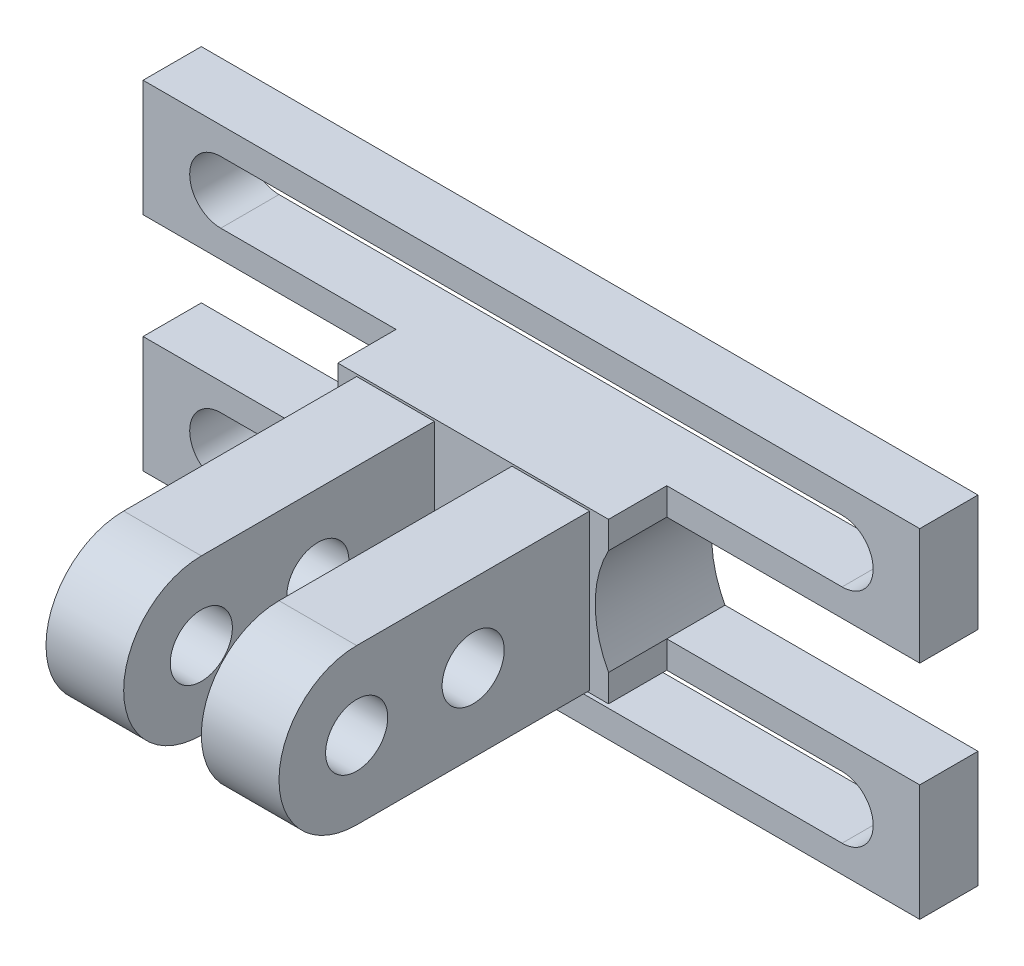
SolidWorks part; units mm, degrees
ref_plane "前视基准面" through (0, 0, 0) normal (0, 0, 1) x (1, 0, 0)
ref_plane "上视基准面" through (0, 0, 0) normal (0, 1, 0) x (1, 0, 0)
ref_plane "右视基准面" through (0, 0, 0) normal (1, 0, 0) x (0, 0, -1)
other "Configuration Table"
sketch "草图1" plane through (0, 0, 0) normal (0, 0, 1) x (1, 0, 0)
  line L0 (30.1537, 0) -> (-30.0932, 0) construction
  line L1 (0, -18.3903) -> (0, 24.264) construction
  line L2 (20, 8.715) -> (20, 2.715)
  line L3 (20, 8.715) -> (-20, 8.715)
  line L5 (20, 2.715) -> (6.9711, 2.715)
  line L6 (-20, 8.715) -> (-20, 2.715)
  line L7 (-20, -8.715) -> (-20, -2.715)
  line L8 (20, -2.715) -> (6.9711, -2.715)
  line L9 (20, -8.715) -> (-20, -8.715)
  line L10 (20, -8.715) -> (20, -2.715)
  line L11 (20, 5.715) -> (-20, 5.715) construction
  line L12 (20, -5.715) -> (-20, -5.715) construction
  line L13 (16, 5.715) -> (-16, 5.715) construction
  line L14 (16, 4.115) -> (-16, 4.115)
  line L15 (16, 7.315) -> (-16, 7.315)
  line L16 (16, -5.715) -> (-16, -5.715) construction
  line L17 (16, -7.315) -> (-16, -7.315)
  line L18 (16, -4.115) -> (-16, -4.115)
  line L21 (-6.9711, 2.715) -> (-20, 2.715)
  line L22 (-6.9711, -2.715) -> (-20, -2.715)
  arc A0 (16, 4.115) -> (16, 7.315) centre (16, 5.715) ccw
  arc A1 (-16, 7.315) -> (-16, 4.115) centre (-16, 5.715) ccw
  arc A2 (16, -7.315) -> (16, -4.115) centre (16, -5.715) ccw
  arc A3 (-16, -4.115) -> (-16, -7.315) centre (-16, -5.715) ccw
  arc A4 (-6.9711, -2.715) -> (-6.9711, 2.715) centre (-12, 0) ccw
  arc A5 (6.9711, -2.715) -> (6.9711, 2.715) centre (12, 0) cw
  point P19 (0, 5.715)
  point P26 (0, -5.715)
  point P37 (0, 2.715)
  point P38 (0, -2.715)
  dimension "D8" = 12
  dimension "D1" = 6
  dimension "D2" = 40
  dimension "D3" = 32
  dimension "D4" = 3.2
  dimension "D5" = 3.2
  dimension "D6" = 32
  dimension "D7" = 11.43
extrude "凸台-拉伸1" add sketch "草图1" along normal blind 3
sketch "草图2" plane through (0, 0, 3) normal (0, 0, 1) x (1, 0, 0)
  line L2 (-16, 4.115) -> (16, 4.115) construction
  line L4 (-6.9711, 2.715) -> (-6.9711, 4.115)
  line L5 (-6.9711, 4.115) -> (6.9711, 4.115)
  line L6 (6.9711, 2.715) -> (6.9711, 4.115)
  line L7 (16, -4.115) -> (-16, -4.115) construction
  line L9 (-6.9711, -2.715) -> (-6.9711, -4.115)
  line L10 (-6.9711, -4.115) -> (6.9711, -4.115)
  line L11 (6.9711, -2.715) -> (6.9711, -4.115)
  arc A0 (6.9711, 2.715) -> (6.9711, -2.715) centre (12, 0) ccw construction
  arc A1 (-6.9711, -2.715) -> (-6.9711, 2.715) centre (-12, 0) ccw construction
  arc A2 (6.9711, 2.715) -> (6.9711, -2.715) centre (12, 0) ccw
  arc A3 (-6.9711, -2.715) -> (-6.9711, 2.715) centre (-12, 0) ccw
extrude "凸台-拉伸2" add sketch "草图2" along normal blind 3
sketch "草图3" plane through (0, 0, 0) normal (1, 0, 0) x (0, 0, -1)
  line L0 (1.8549, 0) -> (-13.3199, 0) construction
  line L1 (-6, 4) -> (-18, 4)
  line L2 (-6, 2.715) -> (-6, -2.715) construction
  line L4 (-6, 0) -> (0, 0) construction
  line L5 (-6, -4) -> (-18, -4)
  line L6 (-6, 4) -> (-6, -4)
  arc A0 (-18, 4) -> (-18, -4) centre (-18, 0) ccw
  circle A1 centre (-18, 0) radius 1.6
  circle A2 centre (-12, 0) radius 1.6
  dimension "D3" = 3.2
  dimension "D4" = 12
  dimension "D5" = 6
  dimension "D6" = 3.2
  dimension "D1" = 4
  dimension "D2" = 12
extrude "凸台-拉伸3" add sketch "草图3" along normal blind 4 from offset 2
mirror "镜向1" about plane through (0, 0, 0) normal (1, 0, 0) of "凸台-拉伸3"
sketch "草图5" plane through (0, 0, 0) normal (0, 0, -1) x (-1, 0, 0)
  line L0 (-6.9711, 2.715) -> (-12, 2.715)
  line L1 (-6.9711, 2.715) -> (-20, 2.715) construction
  line L2 (-12, 2.715) -> (-12, -2.715)
  line L3 (-20, -2.715) -> (-6.9711, -2.715) construction
  line L4 (-12, -2.715) -> (-6.9711, -2.715)
  line L5 (6.9711, 2.715) -> (12, 2.715)
  line L6 (20, 2.715) -> (6.9711, 2.715) construction
  line L7 (12, 2.715) -> (12, -2.715)
  line L8 (6.9711, -2.715) -> (20, -2.715) construction
  line L9 (12, -2.715) -> (6.9711, -2.715)
  arc A0 (-6.9711, -2.715) -> (-6.9711, 2.715) centre (-12, 0) ccw construction
  arc A1 (-6.9711, -2.715) -> (-6.9711, 2.715) centre (-12, 0) ccw
  arc A2 (6.9711, 2.715) -> (6.9711, -2.715) centre (12, 0) ccw construction
  arc A3 (6.9711, 2.715) -> (6.9711, -2.715) centre (12, 0) ccw
extrude "切除-拉伸1" [suppressed] cut sketch "草图5" against normal through all
